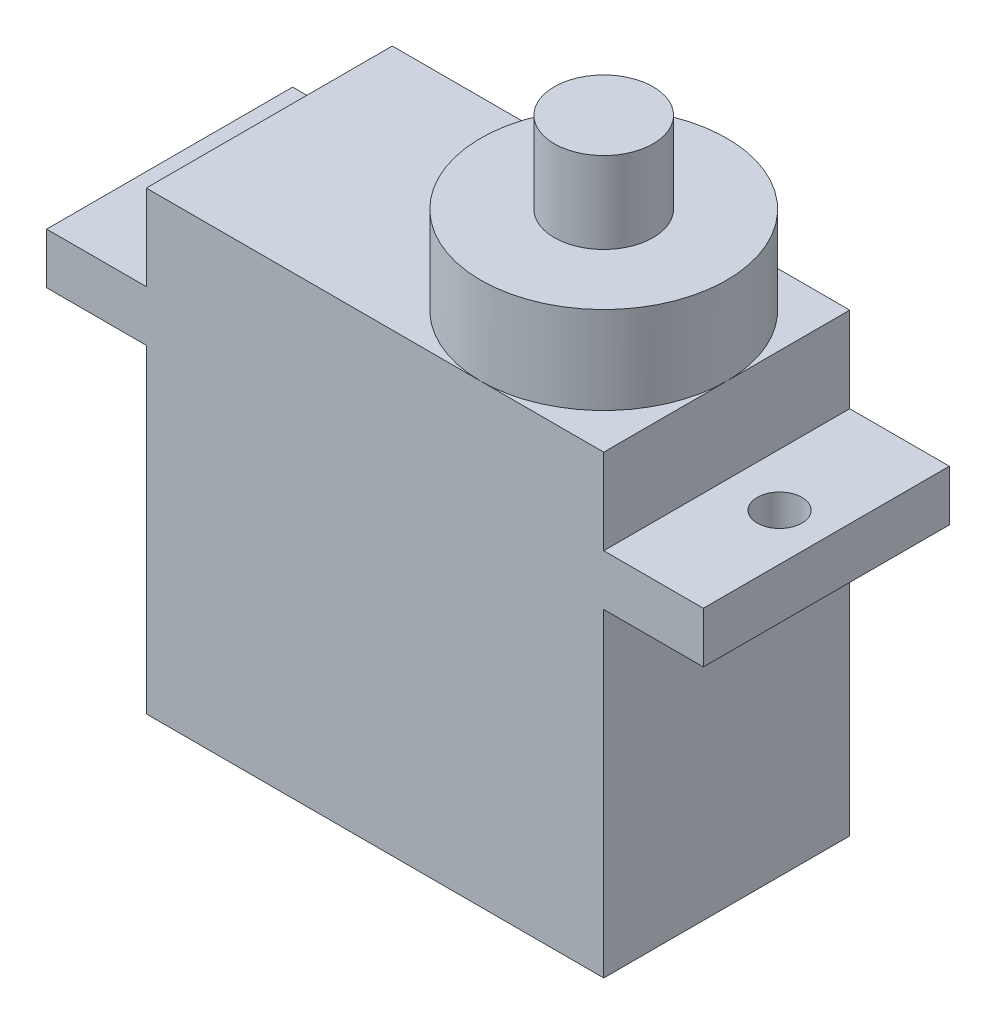
SolidWorks part; units mm, degrees
ref_plane "Спереди" through (0, 0, 0) normal (0, 0, 1) x (1, 0, 0)
ref_plane "Сверху" through (0, 0, 0) normal (0, 1, 0) x (1, 0, 0)
ref_plane "Справа" through (0, 0, 0) normal (1, 0, 0) x (0, 0, -1)
sketch "Эскиз1" plane through (0, 0, 0) normal (0, 0, 1) x (1, 0, 0)
  line L0 (0, 0) -> (22.5, 0)
  line L1 (0, 0) -> (0, 15.7)
  line L2 (22.5, 0) -> (22.5, 15.7)
  line L3 (22.5, 15.7) -> (27.4, 15.7)
  line L4 (0, 15.7) -> (-4.9, 15.7)
  line L5 (27.4, 15.7) -> (27.4, 18.2)
  line L6 (27.4, 18.2) -> (22.5, 18.2)
  line L7 (22.5, 18.2) -> (22.5, 22.4)
  line L8 (22.5, 22.4) -> (0, 22.4)
  line L9 (0, 22.4) -> (0, 18.2)
  line L10 (0, 18.2) -> (-4.9, 18.2)
  line L11 (-4.9, 18.2) -> (-4.9, 15.7)
extrude "Бобышка-Вытянуть1" add sketch "Эскиз1" along normal blind 12.1
sketch "Эскиз3" plane through (0, 22.4, 0) normal (0, 1, 0) x (1, 0, 0)
  circle A0 centre (16.45, -6.05) radius 6.05
extrude "Бобышка-Вытянуть2" add sketch "Эскиз3" along normal blind 4.3
sketch "Эскиз4" plane through (0, 26.7, 0) normal (0, 1, 0) x (1, 0, 0)
  circle A0 centre (16.45, -6.05) radius 2.43
extrude "Бобышка-Вытянуть3" add sketch "Эскиз4" along normal blind 4
sketch "Эскиз5" plane through (0, 18.2, 0) normal (0, 1, 0) x (1, 0, 0)
  circle A0 centre (25.1, -6.05) radius 1.1
  circle A1 centre (-2.6, -6.05) radius 1.1
extrude "Вырез-Вытянуть1" cut sketch "Эскиз5" against normal blind 4
sketch "Эскиз6" plane through (0, 30.7, 0) normal (0, 1, 0) x (1, 0, 0)
  point P0 (16.45, -6.05)
